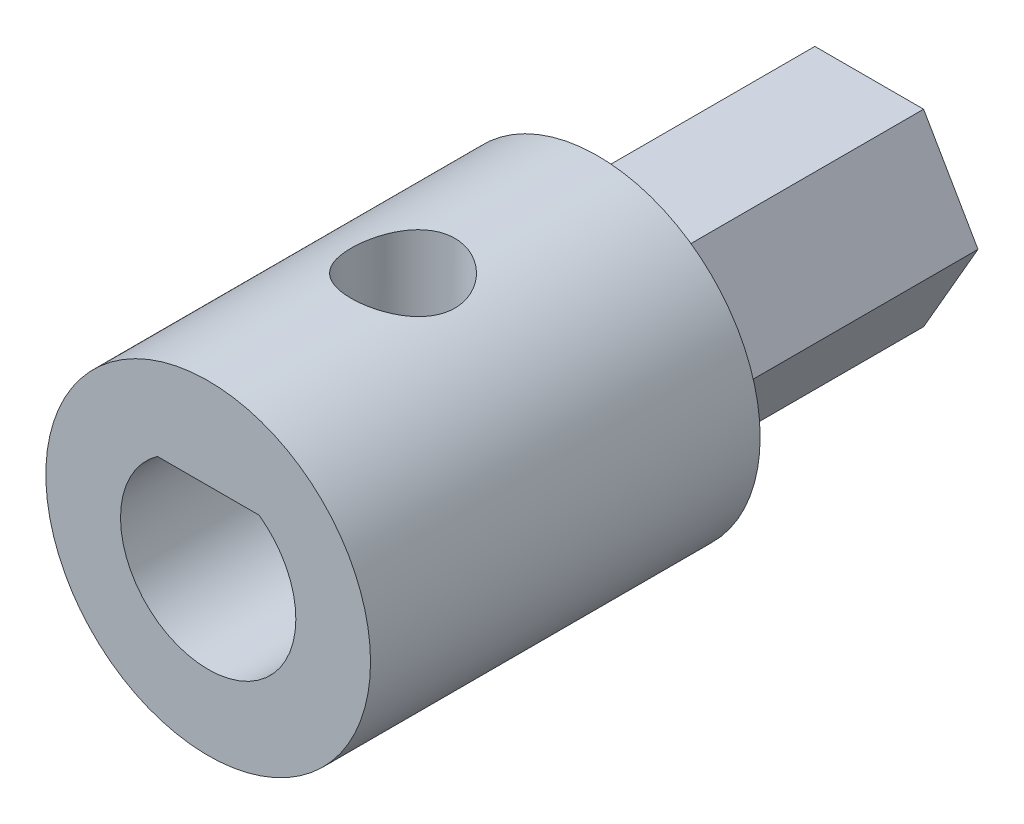
SolidWorks part; units mm, degrees
ref_plane "Front Plane" through (0, 0, 0) normal (0, 0, 1) x (1, 0, 0)
ref_plane "Top Plane" through (0, 0, 0) normal (0, 1, 0) x (1, 0, 0)
ref_plane "Right Plane" through (0, 0, 0) normal (1, 0, 0) x (0, 0, -1)
sketch "Sketch1" plane through (0, 0, 0) normal (0, 0, 1) x (1, 0, 0)
  line L0 (-1.9625, 3.232) -> (2.5375, 3.232) construction
  line L1 (0, 0) -> (-1.675, 2.9012) construction
  line L2 (-1.675, 2.9012) -> (-3.35, 0)
  line L3 (-3.35, 0) -> (-1.675, -2.9012)
  line L4 (-1.675, -2.9012) -> (1.675, -2.9012)
  line L5 (1.675, -2.9012) -> (3.35, 0)
  line L6 (3.35, 0) -> (1.675, 2.9012)
  line L7 (1.675, 2.9012) -> (-1.675, 2.9012)
  circle A0 centre (0, 0) radius 2.9012 construction
  dimension "D1" = 3.35
extrude "Boss-Extrude1" add sketch "Sketch1" along normal blind 8.36
sketch "Sketch3" plane through (0, 0, 8.36) normal (0, 0, 1) x (1, 0, 0)
  circle A0 centre (0, 0) radius 5
  dimension "D1" = 10
extrude "Boss-Extrude2" add sketch "Sketch3" along normal blind 12
sketch "Sketch4" plane through (0, 0, 20.36) normal (0, 0, 1) x (1, 0, 0)
  line L0 (-1.5652, 2.2) -> (1.5652, 2.2)
  arc A0 (-1.5652, 2.2) -> (1.5652, 2.2) centre (0, 0) ccw
  point P3 (0, 0)
  dimension "D2" = 2.7
  dimension "D1" = 2.2
extrude "Cut-Extrude2" cut sketch "Sketch4" against normal through all both and the other way through all
sketch "Sketch5" plane through (0, 0, 0) normal (0, 1, 0) x (1, 0, 0)
  line L0 (0, -8.36) -> (0, -20.36) construction
  line L1 (5, -8.36) -> (-5, -8.36) construction
  line L2 (-5, -20.36) -> (5, -20.36) construction
  circle A0 centre (0, -14.36) radius 1.6
  dimension "D1" = 3.2
extrude "Cut-Extrude3" cut sketch "Sketch5" against normal through all both and the other way through all
equation "\"5mnm\"=8.36"
